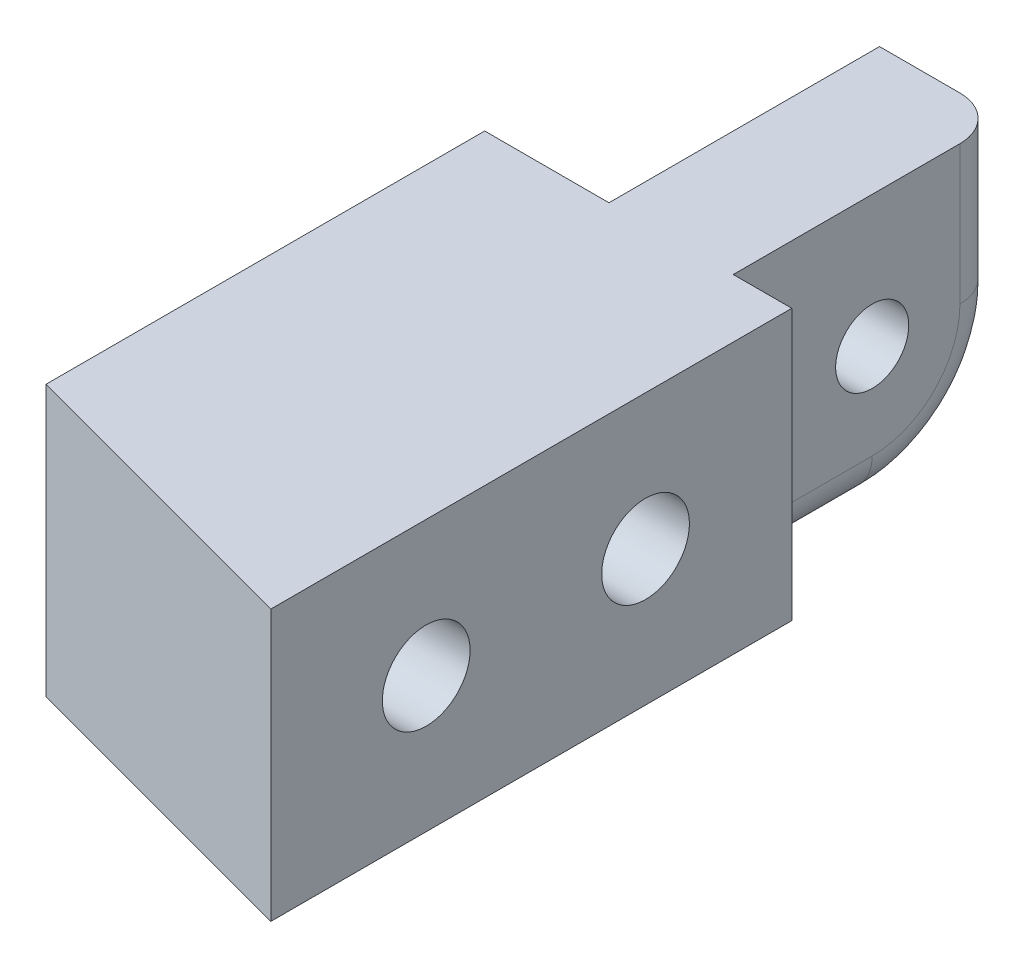
SolidWorks part; units mm, degrees
ref_plane "Front Plane" through (0, 0, 0) normal (0, 0, 1) x (1, 0, 0)
ref_plane "Top Plane" through (0, 0, 0) normal (0, 1, 0) x (1, 0, 0)
ref_plane "Right Plane" through (0, 0, 0) normal (1, 0, 0) x (0, 0, -1)
sketch "Sketch2" plane through (0, 0, 0) normal (0, 1, 0) x (1, 0, 0)
  line L0 (-10.5, 30) -> (-10.5, 0)
  line L1 (-10.5, 0) -> (10.5, -5.6269)
  line L4 (10.5, 30) -> (10.5, -5.6269)
  line L5 (-10.5, 0) -> (10.5, 0) construction
  line L6 (0, 48.5) -> (0, -2.8135) construction
  line L7 (6.5, 30) -> (6.5, 48.5)
  line L8 (6.5, 48.5) -> (-2, 48.5)
  line L9 (-2, 48.5) -> (-2, 30)
  line L10 (-10.5, 30) -> (-2, 30)
  line L11 (6.5, 30) -> (10.5, 30)
  dimension "D1" = 105
  dimension "D2" = 30
  dimension "D3" = 21
  dimension "D4" = 18.5
  dimension "D5" = 4
  dimension "D6" = 8.5
  dimension "D7" = 8.5
extrude "Boss-Extrude1" add sketch "Sketch2" along normal blind 18.5 contours L7 L8 L9 L10 L0 L1 L4 L11
sketch "Sketch3" plane through (6.5, 0, 0) normal (1, 0, 0) x (0, 0, -1)
  line L0 (39.5, 9) -> (39.5, 0) construction
  line L2 (30, 0) -> (48.5, 0) construction
  line L3 (48.5, 9) -> (39.5, 9) construction
  line L4 (48.5, 18.5) -> (48.5, 0) construction
  arc A1 (39.5, 0) -> (48.5, 9) centre (39.5, 9) ccw
  point P12 (39.5, 9)
  dimension "D1" = 9
  dimension "D2" = 9
extrude "Cut-Extrude1" cut sketch "Sketch3" against normal blind 8.5 and the other way through all flip side to cut
fillet "Fillet1" radius 3 3 edges at (6.5, 0, -34.75) (6.5, 2.636, -45.864) (6.5, 13.75, -48.5)
sketch "Sketch4" plane through (0, 0, -48.5) normal (0, 0, -1) x (-1, 0, 0)
  line L0 (-6.5, 18.5) -> (-6.5, 3) construction
  line L2 (-3.5, 0) -> (2, 0) construction
  point P0 (-2.25, 3.5)
  dimension "D1" = 4.25
  dimension "D2" = 3.5
hole_wizard "Ø4.0mm Dowel Hole1" positions "Sketch5" profile "Sketch6" hole size "Ø4.0" standard "DIN"
sketch "Sketch5" plane through (0, 0, -48.5) normal (0, 0, -1) x (-1, 0, 0)
  point P0 (-2.25, 3.5)
sketch "Sketch6" plane through (2.25, 3.5, -48.5) normal (1, 0, 0) x (0, 1, 0)
  line L0 (0, 0) -> (0, 32.7017)
  line L1 (0, 32.7017) -> (2, 31.5)
  line L2 (2, 31.5) -> (2, 0)
  line L5 (2, 0) -> (0, 0)
  line L10 (0, 32.7017) -> (-2, 31.5) construction
  line L11 (0, -6.35) -> (0, 107.95) construction
  dimension "Hole Dia." = 4
  dimension "Hole Depth" = 31.5
  dimension "Drill Angle" = 118
sketch "Sketch8" plane through (0, 0, 0) normal (0, -1, 0) x (1, 0, 0)
  line L0 (0.25, -48.5) -> (4.25, -48.5)
  line L5 (0.25, -48.5) -> (0.25, -31.5)
  line L7 (4.25, -31.5) -> (4.25, -48.5)
  line L8 (3.5, -48.5) -> (-2, -48.5) construction
  line L9 (-2, -39.5) -> (-2, -48.5) construction
  line L10 (2.25, -48.5) -> (2.25, -19) construction
  line L11 (0.25, -22.5) -> (0.25, -19)
  line L12 (4.25, -22.5) -> (4.25, -19)
  line L13 (-10.5, -30) -> (-2, -30) construction
  arc A0 (4.25, -31.5) -> (0.25, -31.5) centre (2.25, -31.5) ccw
  arc A2 (0.25, -22.5) -> (4.25, -22.5) centre (2.25, -22.5) ccw
  arc A4 (4.25, -19) -> (0.25, -19) centre (2.25, -19) ccw
  dimension "D3" = 17
  dimension "D4" = 4
  dimension "D6" = 7.5
  dimension "D1" = 2.25
  dimension "D2" = 4
  dimension "D5" = 3.5
extrude "Cut-Extrude3" cut sketch "Sketch8" against normal blind 3.5
sketch "Sketch9" plane through (10.5, 0, 0) normal (1, 0, 0) x (0, 0, -1)
  line L0 (30, 9.25) -> (-5.6269, 9.25) construction
  line L1 (30, 18.5) -> (30, 0) construction
  line L2 (-5.6269, 18.5) -> (-5.6269, 0) construction
  point P6 (20, 9.25)
  point P7 (5, 9.25)
  dimension "D1" = 10
  dimension "D2" = 15
hole_wizard "Ø6.0mm Dowel Hole1" positions "Sketch10" profile "Sketch11" hole size "Ø6.0" standard "DIN" end condition through all
sketch "Sketch10" plane through (10.5, 0, 0) normal (1, 0, 0) x (0, 0, -1)
  point P0 (20, 9.25)
  point P3 (5, 9.25)
sketch "Sketch11" plane through (10.5, 9.25, -20) normal (0, 1, 0) x (0, 0, -1)
  line L0 (0, 0) -> (0, 21)
  line L1 (0, 21) -> (3, 21)
  line L2 (3, 21) -> (3, 0)
  line L5 (3, 0) -> (0, 0)
  line L11 (0, -6.35) -> (0, 107.95) construction
  dimension "Thru Hole Dia." = 6
  dimension "Thru Hole Depth" = 21
sketch "Sketch12" plane through (6.5, 0, 0) normal (1, 0, 0) x (0, 0, -1)
  line L0 (30, 18.5) -> (45.5, 18.5) construction
  line L1 (48.5, 18.5) -> (48.5, 9) construction
  point P0 (39.5, 9.5)
  point P5 (0, 0)
  dimension "D1" = 9
  dimension "D2" = 9
hole_wizard "Ø5.0mm Dowel Hole1" positions "Sketch13" profile "Sketch14" hole size "Ø5.0" standard "DIN" end condition through all
sketch "Sketch13" plane through (6.5, 0, 0) normal (1, 0, 0) x (0, 0, -1)
  point P0 (39.5, 9.5)
sketch "Sketch14" plane through (6.5, 9.5, -39.5) normal (0, 1, 0) x (0, 0, -1)
  line L0 (0, 0) -> (0, 17)
  line L1 (0, 17) -> (2.5, 17)
  line L2 (2.5, 17) -> (2.5, 0)
  line L5 (2.5, 0) -> (0, 0)
  line L11 (0, -6.35) -> (0, 107.95) construction
  dimension "Thru Hole Dia." = 5
  dimension "Thru Hole Depth" = 17
